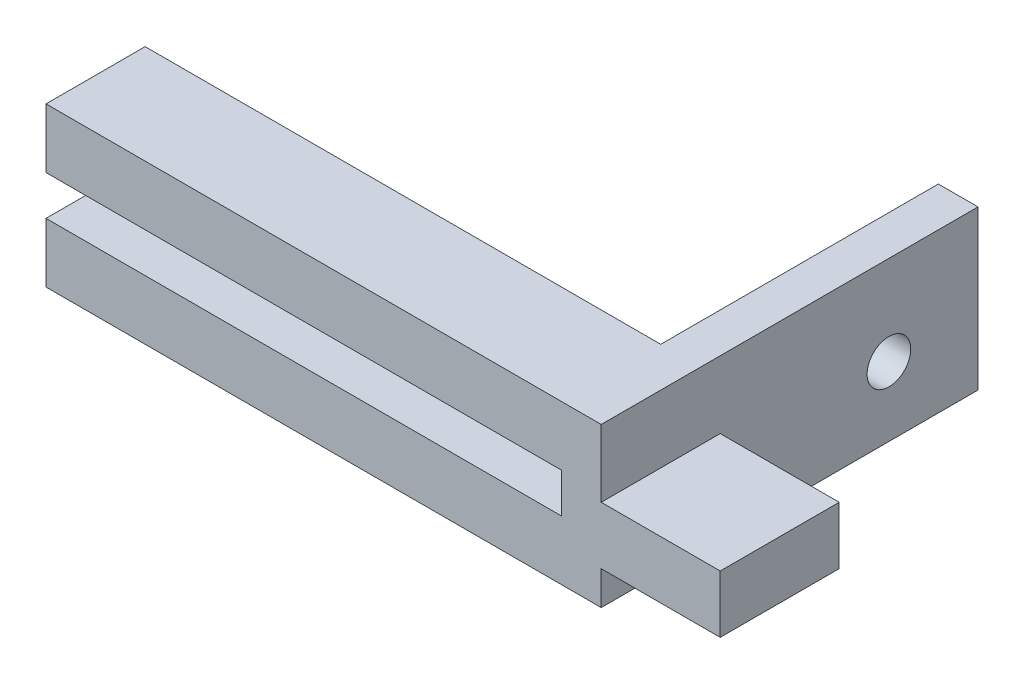
SolidWorks part; units mm, degrees
ref_plane "Front Plane" through (0, 0, 0) normal (0, 0, 1) x (1, 0, 0)
ref_plane "Top Plane" through (0, 0, 0) normal (0, 1, 0) x (1, 0, 0)
ref_plane "Right Plane" through (0, 0, 0) normal (1, 0, 0) x (0, 0, -1)
sketch "Sketch1" plane through (0, 0, 0) normal (1, 0, 0) x (0, 0, -1)
  line L1 (-35.9146, 20.1296) -> (59.0854, 20.1296)
  line L2 (-35.9146, 20.1296) -> (-35.9146, -19.8704)
  line L3 (-35.9146, -19.8704) -> (59.0854, -19.8704)
  line L4 (59.0854, 20.1296) -> (59.0854, -19.8704)
  dimension "D1" = 95
  dimension "D2" = 40
extrude "Boss-Extrude1" add sketch "Sketch1" along normal blind 10
sketch "Sketch4" plane through (0, 0, 0) normal (-1, 0, 0) x (0, 0, 1)
  line L0 (-59.0854, 20.1296) -> (35.9146, 20.1296) construction
  line L1 (10.9146, 20.1296) -> (35.9146, 20.1296)
  line L2 (10.9146, 20.1296) -> (10.9146, 5.1296)
  line L3 (10.9146, 5.1296) -> (35.9146, 5.1296)
  line L4 (35.9146, 20.1296) -> (35.9146, 5.1296)
  line L5 (35.9146, 20.1296) -> (35.9146, -19.8704) construction
  line L6 (35.9146, -19.8704) -> (-59.0854, -19.8704) construction
  line L7 (35.9146, -4.8704) -> (10.9146, -4.8704)
  line L8 (35.9146, -4.8704) -> (35.9146, -19.8704)
  line L9 (35.9146, -19.8704) -> (10.9146, -19.8704)
  line L10 (10.9146, -4.8704) -> (10.9146, -19.8704)
  dimension "D1" = 25
  dimension "D2" = 10
  dimension "D3" = 25
  dimension "D4" = 15
extrude "Boss-Extrude4" add sketch "Sketch4" along normal blind 130
sketch "Sketch5" plane through (0, 0, 0) normal (-1, 0, 0) x (0, 0, 1)
  line L0 (10.9146, -19.8704) -> (-59.0854, -19.8704) construction
  line L1 (-59.0854, -19.8704) -> (-59.0854, 20.1296) construction
  circle A0 centre (-36.6254, -2.4304) radius 5.5
  dimension "D1" = 11
  dimension "D2" = 17.44
  dimension "D3" = 22.46
extrude "Cut-Extrude1" cut sketch "Sketch5" against normal blind 27
sketch "Sketch6" plane through (10, 0, 0) normal (1, 0, 0) x (0, 0, -1)
  line L0 (-35.9146, 20.1296) -> (-35.9146, -19.8704) construction
  line L1 (-5.9146, -2.8704) -> (-35.9146, -2.8704)
  line L2 (-5.9146, -2.8704) -> (-5.9146, 3.1296)
  line L3 (-5.9146, 3.1296) -> (-35.9146, 3.1296)
  line L4 (-35.9146, -2.8704) -> (-35.9146, 3.1296)
  line L5 (-5.9146, -2.8704) -> (-35.9146, 3.1296) construction
  line L6 (-5.9146, 3.1296) -> (-35.9146, -2.8704) construction
  line L8 (-35.9146, -19.8704) -> (59.0854, -19.8704) construction
  point P0 (-20.9146, 0.1296)
  dimension "D1" = 30
  dimension "D2" = 6
  dimension "D3" = 20
extrude "Boss-Extrude5" add sketch "Sketch6" along normal blind 30
sketch "Sketch7" plane through (0, -2.8704, 0) normal (0, -1, 0) x (1, 0, 0)
  line L1 (40, 35.9146) -> (10, 35.9146)
  line L2 (40, 35.9146) -> (40, 5.9146)
  line L3 (40, 5.9146) -> (10, 5.9146)
  line L4 (10, 35.9146) -> (10, 5.9146)
extrude "Boss-Extrude6" add sketch "Sketch7" along normal blind 8.5
